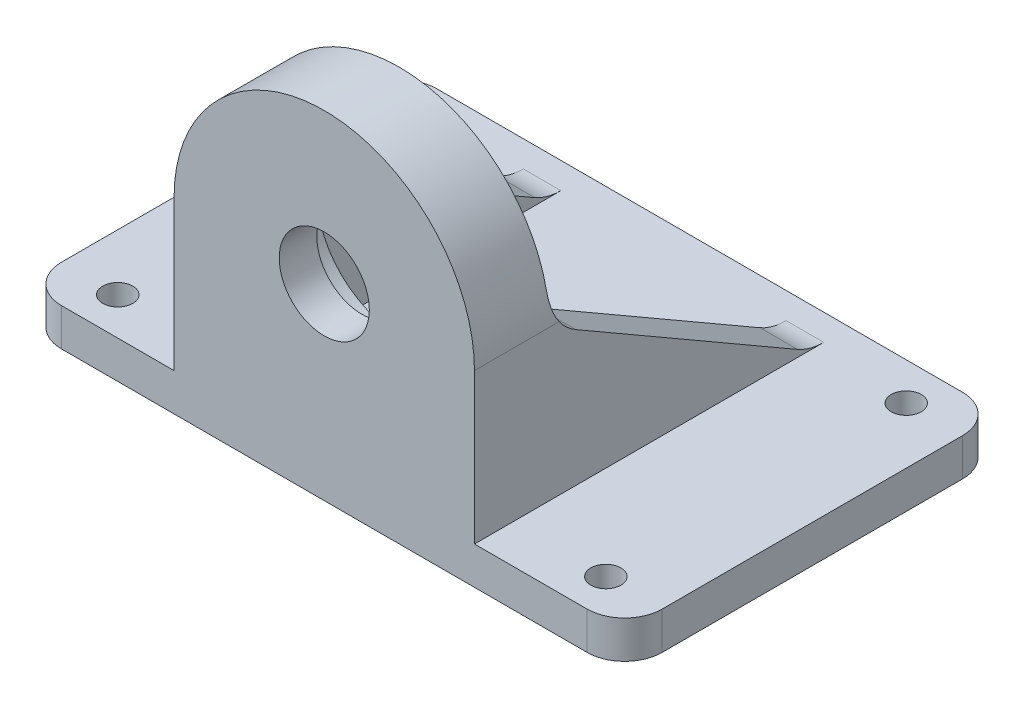
SolidWorks part; units mm, degrees
ref_plane "Front Plane" through (0, 0, 0) normal (0, 0, 1) x (1, 0, 0)
ref_plane "Top Plane" through (0, 0, 0) normal (0, 1, 0) x (1, 0, 0)
ref_plane "Right Plane" through (0, 0, 0) normal (1, 0, 0) x (0, 0, -1)
sketch "Sketch1" plane through (0, 0, 0) normal (0, 1, 0) x (1, 0, 0)
  line L1 (-40, -25) -> (40, -25)
  line L2 (-40, -25) -> (-40, 25)
  line L3 (-40, 25) -> (40, 25)
  line L4 (40, -25) -> (40, 25)
  line L5 (-40, -25) -> (40, 25) construction
  line L6 (-40, 25) -> (40, -25) construction
  point P0 (0, 0)
  dimension "D1" = 50
  dimension "D2" = 80
extrude "Boss-Extrude1" add sketch "Sketch1" along normal blind 5
sketch "Sketch4" plane through (0, 0, 25) normal (0, 0, 1) x (1, 0, 0)
  line L0 (-40, 5) -> (40, 5) construction
  line L1 (0, 0) -> (0, 25) construction
  line L2 (-40, 0) -> (40, 0) construction
  line L3 (-20, 25) -> (-20, 5)
  line L4 (-20, 5) -> (20, 5)
  line L5 (20, 5) -> (20, 25)
  circle A0 centre (0, 25) radius 11
  arc A1 (20, 25) -> (-20, 25) centre (0, 25) ccw
  dimension "D1" = 20
  dimension "D2" = 22
  dimension "D3" = 20
extrude "Boss-Extrude2" add sketch "Sketch4" against normal blind 10
sketch "Sketch5" plane through (0, 0, 25) normal (0, 0, 1) x (1, 0, 0)
  circle A0 centre (0, 25) radius 11
  circle A1 centre (0, 25) radius 6
  dimension "D1" = 12
  dimension "D2" = 22
extrude "Boss-Extrude3" add sketch "Sketch5" against normal blind 5
sketch "Sketch6" plane through (-20, 0, 0) normal (-1, 0, 0) x (0, 0, 1)
  line L0 (15, 25) -> (-19.641, 5)
  line L1 (-25, 5) -> (25, 5) construction
  line L2 (-19.641, 5) -> (15, 5)
  line L3 (15, 5) -> (15, 25)
  dimension "D1" = 30
extrude "Boss-Extrude4" add sketch "Sketch6" against normal blind 5
mirror "Mirror1" about plane through (0, 0, 0) normal (1, 0, 0) of "Boss-Extrude4"
fillet "Fillet2" radius 7 5 edges at (0, 5, 15) (17.5, 25, 15) (-17.5, 25, 15) (-17.5, 5, -19.641) (17.5, 5, -19.641)
sketch "Sketch7" plane through (0, 0, 0) normal (0, -1, 0) x (1, 0, 0)
  line L1 (-32.5, -20) -> (32.5, -20) construction
  line L2 (-32.5, -20) -> (-32.5, 20) construction
  line L3 (-32.5, 20) -> (32.5, 20) construction
  line L4 (32.5, -20) -> (32.5, 20) construction
  line L5 (-32.5, -20) -> (32.5, 20) construction
  line L6 (-32.5, 20) -> (32.5, -20) construction
  circle A0 centre (-32.5, 20) radius 2
  circle A1 centre (-32.5, -20) radius 2
  circle A2 centre (32.5, -20) radius 2
  circle A3 centre (32.5, 20) radius 2
  point P0 (0, 0)
  dimension "D1" = 65
  dimension "D2" = 40
extrude "Cut-Extrude1" cut sketch "Sketch7" against normal blind 5
fillet "Fillet3" radius 5 4 edges at (40, 2.5, 25) (-40, 2.5, 25) (-40, 2.5, -25) (40, 2.5, -25)
